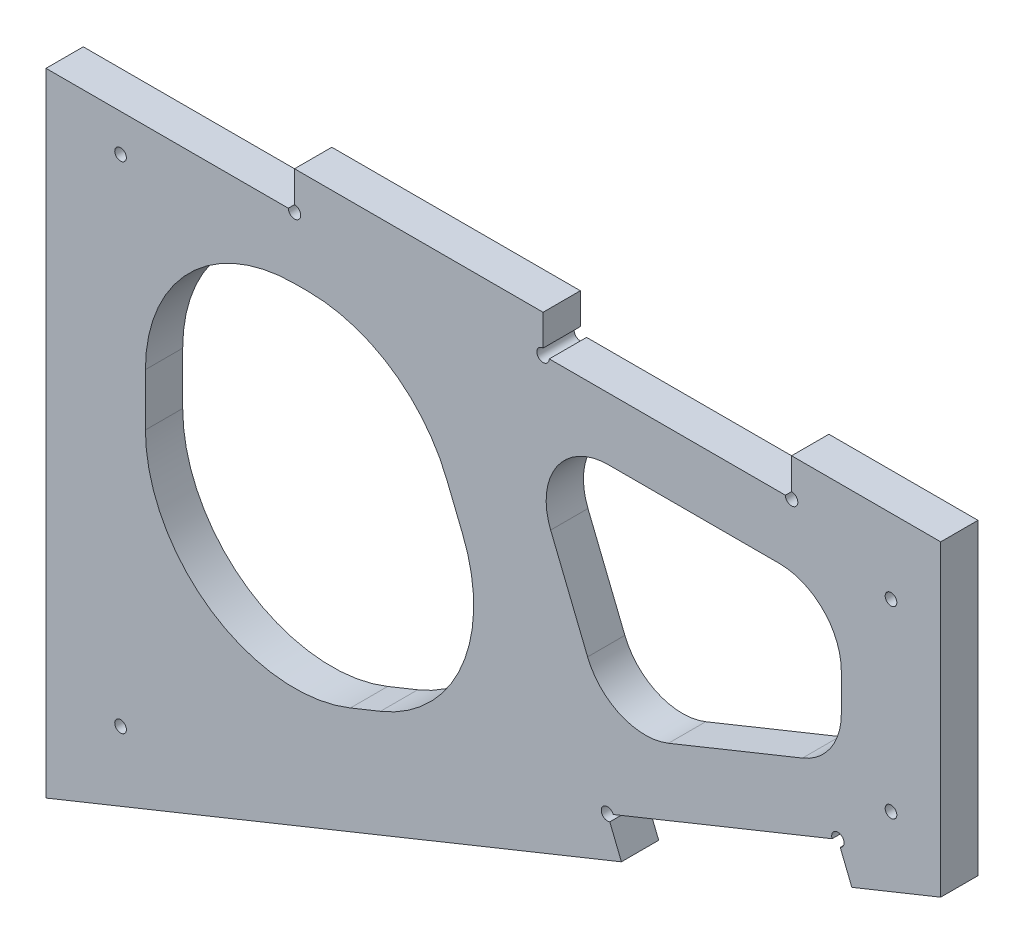
SolidWorks part; units mm, degrees
material "Beech"
ref_plane "Front Plane" through (0, 0, 0) normal (0, 0, 1) x (1, 0, 0)
ref_plane "Top Plane" through (0, 0, 0) normal (0, 1, 0) x (1, 0, 0)
ref_plane "Right Plane" through (0, 0, 0) normal (1, 0, 0) x (0, 0, -1)
sketch "Sketch1" plane through (0, 0, 0) normal (0, 0, 1) x (1, 0, 0)
  line L0 (3140.71, 6983.73) -> (2683.51, 6983.73)
  line L1 (3140.71, 6826.4627) -> (3140.71, 6983.73) construction
  line L2 (3140.71, 6983.73) -> (2683.51, 6983.73) construction
  line L3 (2683.51, 6983.73) -> (2683.51, 6641.7419)
  line L4 (2683.51, 6641.7419) -> (3140.71, 6826.4627)
  line L5 (3140.71, 6826.4627) -> (3140.71, 6983.73)
extrude "Boss-Extrude1" add sketch "Sketch1" along normal blind 19.05
sketch "Sketch6" plane through (0, 0, 0) normal (0, 0, -1) x (-1, 0, 0)
  line L0 (-2925.0567, 6794.1227) -> (-2872.8192, 6923.415) construction
  line L1 (-2923.7645, 6932.93) -> (-3089.91, 6932.93)
  line L2 (-2925.0567, 6794.1227) -> (-2734.31, 6717.056)
  line L4 (-2948.6072, 6803.6377) -> (-2896.3697, 6932.93) construction
  line L5 (-2925.0567, 6794.1227) -> (-2868.9749, 6932.93)
  line L6 (-2972.1577, 6813.1527) -> (-2923.7645, 6932.93)
  line L7 (-2972.1577, 6813.1527) -> (-2919.9202, 6942.445) construction
  line L8 (-3089.91, 6932.93) -> (-3089.91, 6860.7277)
  line L9 (-3089.91, 6860.7277) -> (-2734.31, 6717.056)
  line L10 (-2734.31, 6717.056) -> (-2734.31, 6932.93)
  line L11 (-2734.31, 6932.93) -> (-3089.91, 6932.93)
  line L12 (-3089.91, 6932.93) -> (-3089.91, 6860.7277)
  line L13 (-3089.91, 6860.7277) -> (-2972.1577, 6813.1527)
  line L14 (-2734.31, 6717.056) -> (-2734.31, 6932.93)
  line L15 (-2734.31, 6932.93) -> (-2868.9749, 6932.93)
  point P7 (-2921.8268, 6937.7258)
  point P13 (0, 0)
  point P14 (-2888.5231, 6884.5465)
  point P17 (-2865.1505, 6942.3958)
  point P18 (-2869.0452, 6932.93)
  point P19 (-2921.2763, 6803.6377)
  point P20 (-2966.2753, 6827.712)
  dimension "D2" = 152.4
  dimension "D1" = 50.8
  dimension "D3" = 25.4
  dimension "D4" = 25.4
extrude "Cut-Extrude2" cut sketch "Sketch6" against normal through all
fillet "Fillet1" radius 76.2 4 edges at (2734.31, 6932.93, 9.525) (2868.9749, 6932.93, 9.525) (2925.0567, 6794.1227, 9.525) (2734.31, 6717.056, 9.525)
fillet "Fillet2" radius 31.75 4 edges at (3089.91, 6860.7277, 9.525) (2972.1577, 6813.1527, 9.525) (2923.7645, 6932.93, 9.525) (3089.91, 6932.93, 9.525)
sketch "Sketch2" plane through (0, 0, 0) normal (0, 0, -1) x (-1, 0, 0)
  line L0 (-2683.51, 6964.68) -> (-2810.51, 6964.68) construction
  line L1 (-2810.51, 6964.68) -> (-2810.51, 6983.73) construction
  line L2 (-2810.51, 6983.73) -> (-2683.51, 6983.73) construction
  line L3 (-2683.51, 6983.73) -> (-2683.51, 6964.68) construction
  line L4 (-2937.51, 6964.68) -> (-3064.51, 6964.68) construction
  line L5 (-3064.51, 6964.68) -> (-3064.51, 6983.73) construction
  line L6 (-3064.51, 6983.73) -> (-2937.51, 6983.73) construction
  line L7 (-2937.51, 6983.73) -> (-2937.51, 6964.68) construction
  line L8 (-2977.5519, 6760.5425) -> (-3095.3042, 6808.1176) construction
  line L9 (-3095.3042, 6808.1176) -> (-3088.168, 6825.7804) construction
  line L10 (-3088.168, 6825.7804) -> (-2970.4156, 6778.2054) construction
  line L11 (-2970.4156, 6778.2054) -> (-2977.5519, 6760.5425) construction
  line L12 (-2683.51, 6964.68) -> (-2810.51, 6964.68)
  line L13 (-2810.51, 6964.68) -> (-2810.51, 6983.73)
  line L14 (-2810.51, 6983.73) -> (-2683.51, 6983.73)
  line L15 (-2683.51, 6983.73) -> (-2683.51, 6964.68)
  line L16 (-2937.51, 6964.68) -> (-3064.51, 6964.68)
  line L17 (-3064.51, 6964.68) -> (-3064.51, 6983.73)
  line L18 (-3064.51, 6983.73) -> (-2937.51, 6983.73)
  line L19 (-2937.51, 6983.73) -> (-2937.51, 6964.68)
  line L20 (-2977.5519, 6760.5425) -> (-3095.3042, 6808.1176)
  line L21 (-3095.3042, 6808.1176) -> (-3088.168, 6825.7804)
  line L22 (-3088.168, 6825.7804) -> (-2970.4156, 6778.2054)
  line L23 (-2970.4156, 6778.2054) -> (-2977.5519, 6760.5425)
extrude "Cut-Extrude1" cut sketch "Sketch2" against normal through all
hole_wizard "1/4 (0.25) Diameter Hole1" positions "Sketch3" profile "Sketch4" hole size "1/4" standard "ANSI Inch" end condition through all
sketch "Sketch3" plane through (0, 0, 0) normal (0, 0, -1) x (-1, 0, 0)
  point P0 (-3088.168, 6825.7804)
  point P3 (-2970.4156, 6778.2054)
  point P6 (-2937.51, 6964.68)
  point P9 (-3064.51, 6964.68)
  point P12 (-2810.51, 6964.68)
sketch "Sketch4" plane through (3088.168, 6825.7804, 0) normal (1, 0, 0) x (0, 1, 0)
  line L0 (0, 0) -> (0, 19.05)
  line L1 (0, 19.05) -> (3.175, 19.05)
  line L2 (3.175, 19.05) -> (3.175, 0)
  line L5 (3.175, 0) -> (0, 0)
  line L11 (0, -6.35) -> (0, 107.95) construction
  dimension "Thru Hole Dia." = 6.35
  dimension "Thru Hole Depth" = 19.05
hole_wizard "15/64 (0.23438) Diameter Hole1" positions "Sketch7" profile "Sketch8" hole size "15/64" standard "ANSI Inch" end condition through all
sketch "Sketch7" plane through (0, 0, 0) normal (0, 0, -1) x (0, 1, 0)
  point P0 (6692.5419, 2721.61)
  point P1 (6945.63, 2721.61)
  point P2 (6945.63, 3115.31)
  point P3 (6851.607, 3115.31)
sketch "Sketch8" plane through (2721.61, 6692.5419, 0) normal (1, 0, 0) x (0, 1, 0)
  line L0 (0, 0) -> (0, 19.05)
  line L1 (0, 19.05) -> (2.9766, 19.05)
  line L2 (2.9766, 19.05) -> (2.9766, 0)
  line L3 (2.9766, 0) -> (0, 0)
  line L4 (0, -6.35) -> (0, 107.95) construction
  dimension "Thru Hole Dia." = 5.9533
  dimension "Thru Hole Depth" = 19.05
